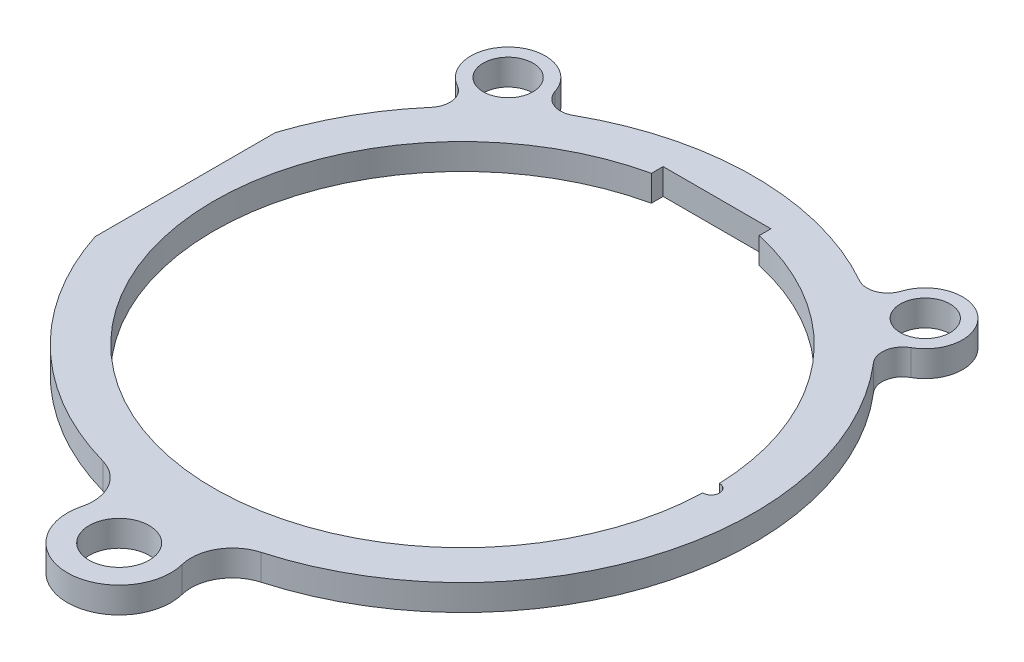
SolidWorks part; units mm, degrees
ref_plane "Front" through (0, 0, 0) normal (0, 0, 1) x (1, 0, 0)
ref_plane "Top" through (0, 0, 0) normal (0, 1, 0) x (1, 0, 0)
ref_plane "Right" through (0, 0, 0) normal (1, 0, 0) x (0, 0, -1)
sketch "Sketch1" plane through (0, 0, 0) normal (0, 1, 0) x (1, 0, 0)
  line L0 (0, -15.24) -> (0, 15.5956) construction
  line L1 (-3.302, 15.5956) -> (3.302, 15.5956)
  line L2 (-3.302, 15.5956) -> (-3.302, 14.878)
  line L3 (3.302, 15.5956) -> (3.302, 14.878)
  circle A0 centre (0, 0) radius 15.24
  circle A1 centre (0, 0) radius 21.59
  dimension "D1" = 30.48
  dimension "D3" = 30.8356
  dimension "D4" = 6.604
  dimension "D2" = 6.35
extrude "Boss-Extrude1" add sketch "Sketch1" along normal mid plane 1.5875 contours A1 A0 L2 L1 L3
sketch "Sketch2" plane through (0, 0.7937, 0) normal (0, 1, 0) x (1, 0, 0)
  line L0 (0, 18.415) -> (0, -18.415) construction
  line L1 (0, -15.24) -> (0, -21.59) construction
  circle A0 centre (0, 18.415) radius 1.4224
  circle A1 centre (0, -18.415) radius 1.4224
  arc A2 (-3.302, 14.878) -> (3.302, 14.878) centre (0, 0) ccw construction
  circle A3 centre (0, 0) radius 21.59 construction
  dimension "D1" = 2.8448
extrude "Cut-Extrude1" cut sketch "Sketch2" against normal through all
sketch "Sketch3" plane through (0, 0.7937, 0) normal (0, 1, 0) x (1, 0, 0)
  line L0 (-20.8712, 5.5245) -> (-16.9841, 5.5245)
  line L1 (-16.9841, 5.5245) -> (-16.9841, -5.5245)
  line L2 (-16.9841, -5.5245) -> (-20.8712, -5.5245)
  line L3 (-16.9841, -5.5245) -> (-20.8712, -5.5245) construction
  line L4 (-20.8712, 5.5245) -> (-16.9841, 5.5245) construction
  circle A0 centre (0, 0) radius 21.59 construction
  arc A1 (-20.8712, 5.5245) -> (-20.8712, -5.5245) centre (0, 0) ccw
extrude "Cut-Extrude2" cut sketch "Sketch3" against normal through all
sketch "Sketch4" plane through (0, 0.7937, 0) normal (0, 1, 0) x (1, 0, 0)
  line L0 (15.748, 0) -> (-15.24, 0) construction
  circle A0 centre (15.24, 0) radius 0.508
  arc A1 (-3.302, 14.878) -> (3.302, 14.878) centre (0, 0) ccw construction
  dimension "D1" = 30.988
extrude "Cut-Extrude3" cut sketch "Sketch4" against normal through all
sketch "Sketch5" plane through (0, 0.7937, 0) normal (0, 1, 0) x (1, 0, 0)
  line L0 (-12.3201, -16.1591) -> (12.3201, 16.1591) construction
  line L1 (-13.8351, -15.0041) -> (10.8052, 17.3141)
  line L2 (-10.8052, -17.3141) -> (13.8351, 15.0041)
  line L3 (16.1591, -12.3201) -> (-16.1591, 12.3201) construction
  line L4 (15.0041, -13.8351) -> (-17.3141, 10.8052)
  line L5 (17.3141, -10.8052) -> (-15.0041, 13.8351)
  line L6 (0, 0) -> (2.7145, -20.1379) construction
  line L7 (1.8879, 0.2545) -> (4.6025, -19.8834)
  line L8 (-1.8879, -0.2545) -> (0.8266, -20.3924)
  line L9 (-16.1591, 12.3201) -> (12.3201, 16.1591) construction
  circle A0 centre (0, 0) radius 17.86
  arc A1 (-13.8351, -15.0041) -> (-10.8052, -17.3141) centre (-12.3201, -16.1591) ccw
  arc A2 (13.8351, 15.0041) -> (10.8052, 17.3141) centre (12.3201, 16.1591) ccw
  circle A3 centre (12.3201, 16.1591) radius 1.0922
  circle A4 centre (-12.3201, -16.1591) radius 1.0922
  arc A5 (15.0041, -13.8351) -> (17.3141, -10.8052) centre (16.1591, -12.3201) ccw
  arc A6 (-15.0041, 13.8351) -> (-17.3141, 10.8052) centre (-16.1591, 12.3201) ccw
  circle A7 centre (-16.1591, 12.3201) radius 1.0922
  circle A8 centre (16.1591, -12.3201) radius 1.0922
  arc A9 (1.8879, 0.2545) -> (-1.8879, -0.2545) centre (0, 0) ccw
  arc A10 (0.8266, -20.3924) -> (4.6025, -19.8834) centre (2.7145, -20.1379) ccw
  circle A11 centre (2.7145, -20.1379) radius 1.0922
  arc A12 (16.1591, -12.3201) -> (2.7145, -20.1379) centre (0, 0) cw construction
  point P6 (0, 0)
  point P17 (0, 0)
  point P26 (1.3573, -10.0689)
  line M7 (-20.8712, 5.5245) -> (-16.9841, 5.5245)
  line M9 (-16.9841, -5.5245) -> (-20.8712, -5.5245)
  arc M10 (-20.8712, -5.5245) -> (-20.8712, 5.5245) centre (0, 0) ccw
  circle M11 centre (0, -18.415) radius 1.4224
  circle M12 centre (0, 18.415) radius 1.4224
  dimension "D2" = 3.81
  dimension "D1" = 3.81
extrude "Cut-Extrude4" cut sketch "Sketch5" against normal through all contours A6 A0 L4 M10 M7 | L5 A6 L4 A0 A7 M10 | A7 | A6 L5 A0 L1 A2 M12 M10 | A3 | L2 A2 L1 A0 A3 M10 | A5 A2 L2 A0 L5 M10 | A10 A5 L4 A0 L7 M10 | A5 L5 A0 L4 A8 M10 | A8 | A11 | A10 L7 A0 L8 A11 M10 M11 | A10 L8 A0 L2 A1 M11 M10 | A1 L1 A0 M9 M10 | A4 | A1 L2 A0 L1 A4 M10
sketch "Sketch6" plane through (0, 0.7937, 0) normal (0, 1, 0) x (1, 0, 0)
  line L0 (0, 17.86) -> (16.5405, 17.86) construction
  circle A0 centre (0, 0) radius 17.86
  circle A1 centre (12.7793, 15.574) radius 1.524
  circle A2 centre (-12.7793, 15.574) radius 1.524
  circle A3 centre (12.7793, 15.574) radius 2.286
  circle A4 centre (-12.7793, 15.574) radius 2.286
  circle A5 centre (9.3946, 16.6642) radius 1.27
  circle A6 centre (14.5094, 12.4672) radius 1.27
  circle A7 centre (-9.3946, 16.6642) radius 1.27
  circle A8 centre (-14.5094, 12.4672) radius 1.27
  circle A9 centre (0, -21.035) radius 1.8415
  circle A10 centre (0, -21.035) radius 3.175
  circle A11 centre (5.5404, -19.6332) radius 2.54
  circle A12 centre (-5.5404, -19.6332) radius 2.54
  arc M9 (-1.2889, -17.8134) -> (1.2889, -17.8134) centre (0, -18.415) cw
  arc M10 (1.2889, -17.8134) -> (1.2889, 17.8134) centre (0, 0) ccw
  arc M11 (1.2889, 17.8134) -> (-1.2889, 17.8134) centre (0, 18.415) cw
  dimension "D1" = 3.048
  dimension "D2" = 4.572
  dimension "D3" = 2.54
  dimension "D4" = 3.683
  dimension "D5" = 6.35
  dimension "D6" = 5.08
extrude "Boss-Extrude2" add sketch "Sketch6" against normal up to vertex contours A3 A1 | A6 A3 A0 | A5 A0 A3 | A7 A4 A0 | A4 A2 | A8 A0 A4 | A10 A9 | A11 A0 A10 M10 | A0 M9 | A12 A10 A0 | A0 M11
